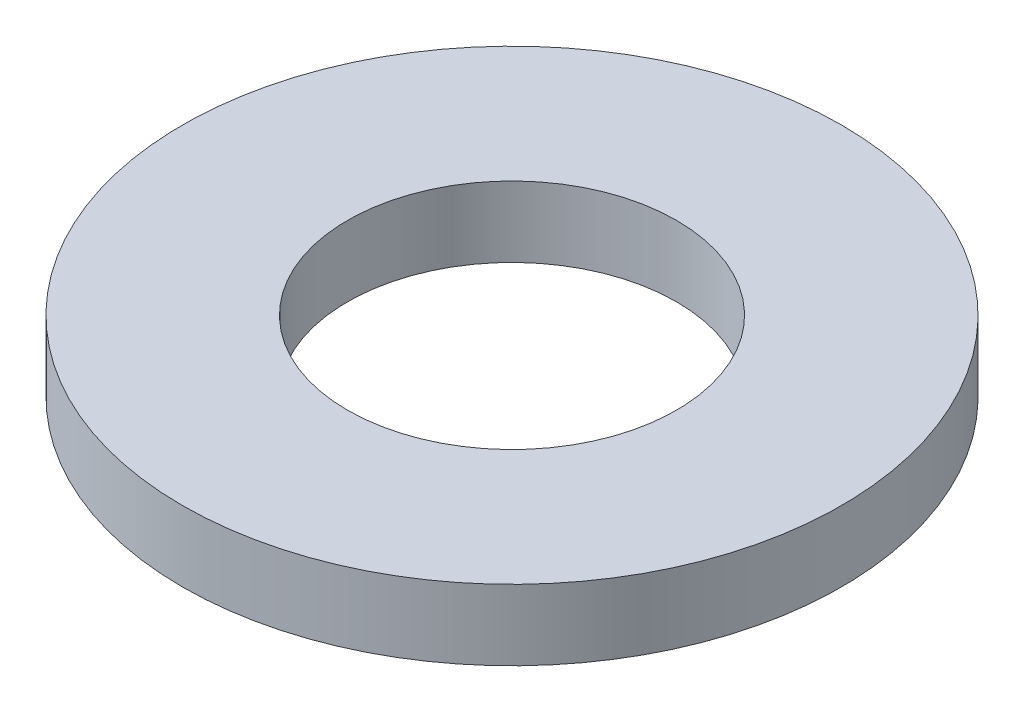
SolidWorks part; units mm, degrees
ref_plane "Front Plane" through (0, 0, 0) normal (0, 0, 1) x (1, 0, 0)
ref_plane "Top Plane" through (0, 0, 0) normal (0, 1, 0) x (1, 0, 0)
ref_plane "Right Plane" through (0, 0, 0) normal (1, 0, 0) x (0, 0, -1)
sketch "Sketch1" plane through (0, 0, 0) normal (0, 1, 0) x (1, 0, 0)
  circle A0 centre (0, 0) radius 4.5085
  dimension "D1" = 9.017
extrude "Boss-Extrude1" add sketch "Sketch1" along normal blind 0.9652
hole_wizard "M4 Clearance Hole1" positions "Sketch2" profile "Sketch3" hole size "M4" standard "ANSI Metric" end condition through all
sketch "Sketch2" plane through (0, 0.9652, 0) normal (0, 1, 0) x (1, 0, 0)
  point P0 (0, 0)
sketch "Sketch3" plane through (0, 0.9652, 0) normal (1, 0, 0) x (0, 0, 1)
  line L0 (0, 0) -> (0, 0.9652)
  line L1 (0, 0.9652) -> (2.25, 0.9652)
  line L2 (2.25, 0.9652) -> (2.25, 0)
  line L5 (2.25, 0) -> (0, 0)
  line L11 (0, -6.35) -> (0, 107.95) construction
  dimension "Thru Hole Dia." = 4.5
  dimension "Thru Hole Depth" = 0.9652
